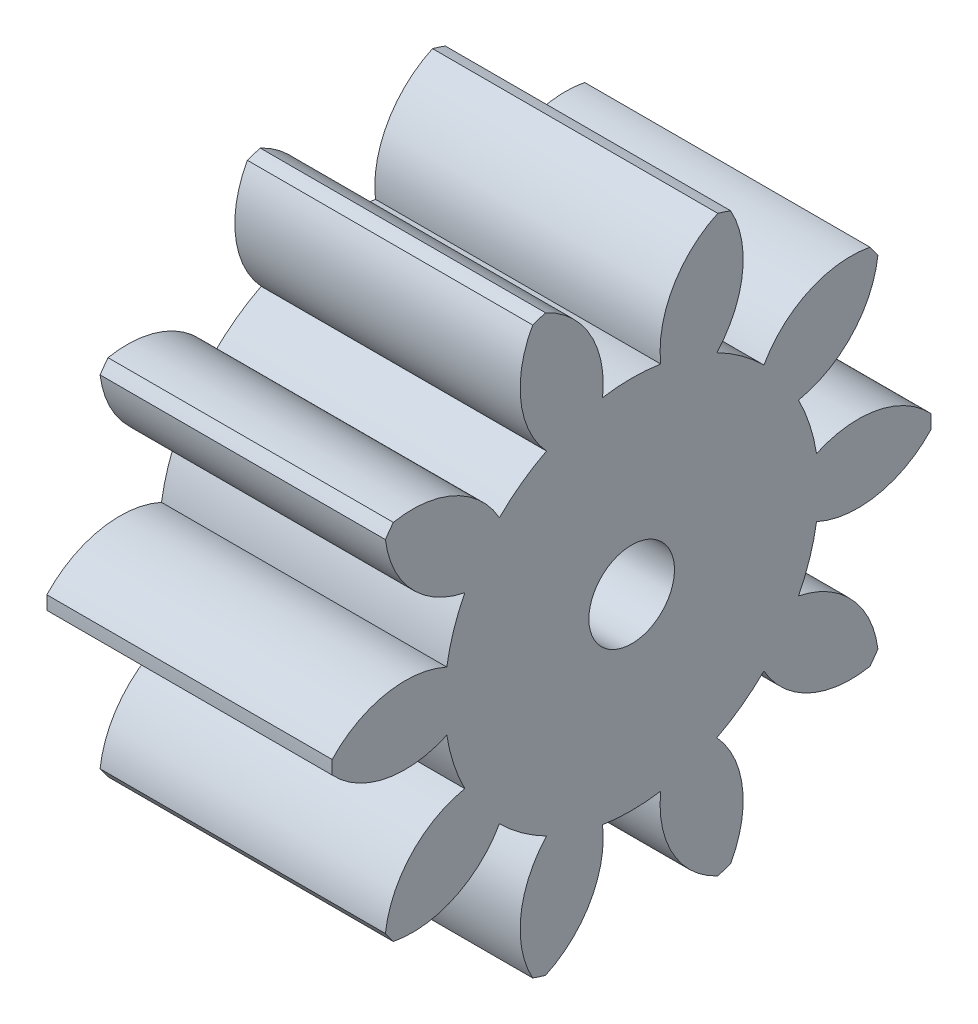
SolidWorks part; units mm, degrees
ref_plane "Plane1" through (0, 0, 0) normal (0, 0, 1) x (1, 0, 0)
ref_plane "Plane2" through (0, 0, 0) normal (0, 1, 0) x (1, 0, 0)
ref_plane "Plane3" through (0, 0, 0) normal (1, 0, 0) x (0, 0, -1)
sketch "HoldingSke" plane through (0, 0, 0) normal (0, 1, 0) x (1, 0, 0)
  line L0 (0, 0) -> (0.5627, -0.0992)
  line L1 (-15, 0) -> (100, 0) construction
  line L2 (0, 0) -> (-2.1039, 2.3779)
  line L3 (0, 0) -> (-11.863, 4.5341)
  line L4 (0, 0) -> (8.5048, 1.4996)
  line L5 (0, 0) -> (-46.8476, -17.4728)
  line L6 (0, 0) -> (-8.2896, -5.593)
  line L7 (-2.1039, 2.3779) -> (8.6586, 51.2059)
  line L8 (-76.2, 54.61) -> (-75.7, 54.61)
  line L9 (-71.009, 38.7566) -> (-53.1078, 45.2721)
  line L10 (-76.2, 71.12) -> (104.1128, 71.12)
  line L11 (0, 0) -> (-10, 0)
  line L12 (-76.2, 101.6) -> (-76.147, 101.6)
  line L13 (24.9733, 27.94) -> (52.9518, 28.4284)
  line L14 (24.9733, 27.94) -> (24.9743, 27.94)
  line L15 (24.9733, 27.94) -> (100.4006, 29.5858)
  line L16 (-63.627, -1.75) -> (-12.827, -1.75)
  circle A0 centre (0, 0) radius 1.5
  circle A1 centre (0, 0) radius 6.5615
  circle A2 centre (0, 0) radius 37.5
  circle A3 centre (0, 0) radius 1.5
  dimension "MHD" = 13.123
  dimension "Hub_dia" = 75
  dimension "Bore" = 3
  dimension "MBD" = 3
  dimension "Num_teeth" = 10
  dimension "Pitch" = 0.5714
  dimension "Overall_len" = 50
  dimension "Show_teeth" = 10
  dimension "Thickness" = 10
  dimension "OAL" = 50.0001
  dimension "T_dim" = 0.5
  dimension "Ap" = 20
  dimension "H" = 19.05
  dimension "Pitch_radius" = 180.3128
  dimension "Width" = 10
  dimension "Backlash" = 0.053
  dimension "Addendum_fac" = 1
  dimension "Dedendum_fac" = 1.25
  dimension "Clearance_fac" = 0.25
  dimension "Dedendum_add" = 0.001
  dimension "Module" = 1.75
sketch "BasProSke" plane through (0, 0, 0) normal (0, 1, 0) x (1, 0, 0)
  line L0 (-10, 0) -> (60, 0) construction
  line L1 (0, 0) -> (0, 10.5)
  line L2 (0, 0) -> (10, 0)
  line L3 (10, 0) -> (10, 10.5)
  line L4 (10, 10.5) -> (0, 10.5)
  dimension "Thickness" = 10
  dimension "Diameter" = 21
revolve "Base-Revolve" add sketch "BasProSke" angle 360 about L0
sketch "TooCutSke" plane through (0, 0, 0) normal (1, 0, 0) x (0, 0, -1)
  line L1 (0, 0) -> (0, 107) construction
  line L2 (0, 0) -> (-1.4614, 8.6271) construction
  line L3 (0, 0) -> (-5.35, 16.4656) construction
  line L4 (-1.4614, 8.6271) -> (-2.675, 8.2328) construction
  arc A0 (1.0196, 6.4818) -> (-1.0196, 6.4818) centre (0, 0) ccw
  arc A1 (3.0536, 10.0727) -> (-3.0536, 10.0727) centre (0, 0) ccw
  circle A2 centre (0, 0) radius 8.75 construction
  circle A3 centre (0, 0) radius 8.2223 construction
  arc A4 (-1.0196, 6.4818) -> (-3.0536, 10.0727) centre (-4.4964, 6.8839) ccw
  arc A5 (3.0536, 10.0727) -> (1.0196, 6.4818) centre (4.4964, 6.8839) ccw
  dimension "Root_dia" = 13.123
  dimension "Overcut_dia" = 21.0508
  dimension "Pitch_dia" = 17.5
  dimension "Base_dia" = 16.4446
  dimension "Flank_rad" = 3.5
  dimension "Half_ang" = 18
  dimension "Half_CT" = 1.2761
extrude "ToothCut" cut sketch "TooCutSke" along normal through all
fillet "Breaks" [suppressed] radius 0.035
fillet "RootFillets" [suppressed] radius 0.4385
pattern_circular "TeethCuts" count 10 every 36 about axis through (-10, 0, 0) along (1, 0, 0) of "ToothCut", "RootFillets", "Breaks"
sketch "HubNeaOneSke" plane through (0, 0, 0) normal (-1, 0, 0) x (0, 0, 1)
  circle A0 centre (0, 0) radius 6.5615
  dimension "Diameter" = 13.123
extrude "HubNearOne" [suppressed] add sketch "HubNeaOneSke" along normal blind 40.0001
sketch "HubNeaBotSke" plane through (0, 0, 0) normal (-1, 0, 0) x (0, 0, 1)
  circle A0 centre (0, 0) radius 6.5615
  dimension "Diameter" = 13.123
extrude "HubNearBoth" [suppressed] add sketch "HubNeaBotSke" along normal blind 20
ref_plane "FarPln" through (10, 0, 0) normal (1, 0, 0) x (0, 0, -1)
sketch "HubFarSke" plane through (10, 0, 0) normal (1, 0, 0) x (0, 0, -1)
  circle A0 centre (0, 0) radius 6.5615
  dimension "Diameter" = 13.123
extrude "HubFar" [suppressed] add sketch "HubFarSke" along normal blind 20
sketch "BorSke" plane through (0, 0, 0) normal (1, 0, 0) x (0, 0, -1)
  circle A0 centre (0, 0) radius 1.5
  dimension "Diameter" = 3
extrude "Bore" cut sketch "BorSke" along normal mid plane 100.0001
sketch "KeySke" plane through (0, 0, 0) normal (1, 0, 0) x (0, 0, -1)
  line L0 (-0.6, 0) -> (-0.6, 2)
  line L1 (-0.6, 2) -> (0.6, 2)
  line L2 (0.6, 2) -> (0.6, 0)
  line L3 (0, 0) -> (0, 34) construction
  line L4 (-0.6, 0) -> (0.6, 0)
  dimension "Offset" = 2
  dimension "Width" = 1.2
extrude "Keyway" [suppressed] cut sketch "KeySke" along normal mid plane 100.0001
pattern_circular "Keyway2" [suppressed] count 2 every 90 about axis through (-10, 0, 0) along (1, 0, 0)
equation "' \"Module@HoldingSke\" = 6.35"
equation "' \"Num_teeth@HoldingSke\" = 12"
equation "' \"Ap@HoldingSke\" =  20"
equation "' \"Ap@HoldingSke\" = 20"
equation "' \"Width@HoldingSke\" = 0.5 * 25.4"
equation "' \"Hub_dia@HoldingSke\"= 1 * 25.4"
equation "' \"Hub_dia@HoldingSke\" = 1 * 25.4"
equation "' \"Overall_len@HoldingSke\" = 1.0 * 25.4"
equation "' \"Bore@HoldingSke\" = 0.75 * 25.4"
equation "' \"T_dim@HoldingSke\" = 0.1 * 25.4"
equation "' \"Width@KeySke\" = 0.25 * 25.4"
equation "' \"Show_teeth@HoldingSke\" = 13"
equation "' \"Backlash@HoldingSke\" = 0.009 * 25.4"
equation "' \"Addendum_fac@HoldingSke\" = 1.0"
equation "' \"Dedendum_fac@HoldingSke\" = 1.25"
equation "' \"Dedendum_add@HoldingSke\" = 0.00005 * 25.4"
equation "' \"Clearance_fac@HoldingSke\" = 0.25"
equation "\"Pitch@HoldingSke\" = 1 / \"Module@HoldingSke\""
equation "\"Overcut_dia@TooCutSke\" = (\"Num_teeth@HoldingSke\" + 2 * \"Addendum_fac@HoldingSke\") / \"Pitch@HoldingSke\" + 0.002 * 25.4"
equation "\"Pitch_dia@TooCutSke\" = \"Num_teeth@HoldingSke\" / \"Pitch@HoldingSke\""
equation "\"Base_dia@TooCutSke\" = \"Num_teeth@HoldingSke\" / \"Pitch@HoldingSke\" * cos((\"Ap@HoldingSke\"  * 3.14159265 / 180))"
equation "\"Root_dia@TooCutSke\" = (\"Num_teeth@HoldingSke\" + 2) / \"Pitch@HoldingSke\" - 2 * (\"Addendum_fac@HoldingSke\" + \"Dedendum_fac@HoldingSke\") / \"Pitch@HoldingSke\" - \"Dedendum_add@HoldingSke\" * 2"
equation "\"Half_ang@TooCutSke\" = 180 / \"Num_teeth@HoldingSke\""
equation "\"Half_CT@TooCutSke\" = \"Num_teeth@HoldingSke\" / \"Pitch@HoldingSke\" * sin((3.14159265 / 2 / \"Num_teeth@HoldingSke\")) / 2 - 7 * \"Backlash@HoldingSke\" / 4"
equation "\"Flank_rad@TooCutSke\" = \"Num_teeth@HoldingSke\" / \"Pitch@HoldingSke\" / 5"
equation "\"Radius@RootFillets\" = \"Clearance_fac@HoldingSke\" / \"Pitch@HoldingSke\" + \"Dedendum_add@HoldingSke\""
equation "\"Break_rad@Breaks\" = 0.02 / \"Pitch@HoldingSke\""
equation "\"Thickness@HoldingSke\" = \"Width@HoldingSke\""
equation "\"OAL@HoldingSke\" = \"Thickness@HoldingSke\""
equation "\"MHD@HoldingSke\" = (\"Num_teeth@HoldingSke\" + 2) / \"Pitch@HoldingSke\" - 2 * (\"Addendum_fac@HoldingSke\" + \"Dedendum_fac@HoldingSke\")  / \"Pitch@HoldingSke\" - \"Dedendum_add@HoldingSke\" * 2"
equation "\"MBD@HoldingSke\" = (\"Num_teeth@HoldingSke\" + 2) / \"Pitch@HoldingSke\" - 2 * (\"Addendum_fac@HoldingSke\" + \"Dedendum_fac@HoldingSke\")  / \"Pitch@HoldingSke\" - \"Dedendum_add@HoldingSke\" * 2 - 0.002 * 25.4"
equation "\"MHD@HoldingSke\" = ((sgn( \"MHD@HoldingSke\" - \"Hub_dia@HoldingSke\" )-1)*( \"MHD@HoldingSke\" - \"Hub_dia@HoldingSke\" ))/-2+ \"Hub_dia@HoldingSke\""
equation "\"MBD@HoldingSke\" = ((sgn( \"MBD@HoldingSke\" - \"Bore@HoldingSke\" )-1)*( \"MBD@HoldingSke\" - \"Bore@HoldingSke\" ))/-2+ \"Bore@HoldingSke\""
equation "\"OAL@HoldingSke\" = ((sgn( \"OAL@HoldingSke\" - \"Overall_len@HoldingSke\" )+1)*( \"OAL@HoldingSke\" - \"Overall_len@HoldingSke\" ))/2 + \"Overall_len@HoldingSke\" + 0.000002 * 25.4"
equation "\"Num_teeth@TeethCuts\" = int( \"Show_teeth@HoldingSke\" ) + 1"
equation "\"Num_teeth@TeethCuts\" = ((sgn( \"Num_teeth@TeethCuts\" - \"Num_teeth@HoldingSke\" )-1)*( \"Num_teeth@TeethCuts\" - \"Num_teeth@HoldingSke\" ))/-2+ \"Num_teeth@HoldingSke\""
equation "\"Num_teeth@TeethCuts\" = ((sgn( \"Num_teeth@TeethCuts\" - 2.0)+1)*( \"Num_teeth@TeethCuts\" - 2.0))/2 +2.0"
equation "\"Angle@TeethCuts\" = 360.0 / \"Num_teeth@HoldingSke\""
equation "\"Diameter@BasProSke\" = (\"Num_teeth@HoldingSke\" + 2 * \"Addendum_fac@HoldingSke\") / \"Pitch@HoldingSke\""
equation "\"Thickness@BasProSke\"  = \"Thickness@HoldingSke\""
equation "' \"Fillet_rad@BasProSke\" =  \"Thickness@HoldingSke\" * 0.05"
equation "' \"Fillet_rad@BasProSke\" = \"Thickness@HoldingSke\" * 0.05"
equation "\"MHD@HoldingSke\" = ((sgn( \"MHD@HoldingSke\" - \"Root_dia@TooCutSke\" )-1)*( \"MHD@HoldingSke\" - \"Root_dia@TooCutSke\" ))/-2+ \"Root_dia@TooCutSke\""
equation "\"Diameter@HubNeaOneSke\" = \"MHD@HoldingSke\""
equation "\"Length@HubNearOne\" = \"OAL@HoldingSke\" - \"Thickness@BasProSke\""
equation "\"Diameter@HubNeaBotSke\" = \"MHD@HoldingSke\""
equation "\"Length@HubNearBoth\" = ( \"OAL@HoldingSke\" - \"Thickness@BasProSke\" ) / 2.0"
equation "\"Thickness@FarPln\" = \"Thickness@BasProSke\""
equation "\"Diameter@HubFarSke\" = \"MHD@HoldingSke\""
equation "\"Length@HubFar\" = ( \"OAL@HoldingSke\" - \"Thickness@BasProSke\" ) / 2.0"
equation "\"Diameter@BorSke\" = \"MBD@HoldingSke\""
equation "\"D1@Bore\" = \"OAL@HoldingSke\" * 2.0"
equation "\"D1@Keyway\" = \"OAL@HoldingSke\" * 2.0"
equation "\"Offset@KeySke\" = \"T_dim@HoldingSke\" + \"MBD@HoldingSke\" / 2.0"
